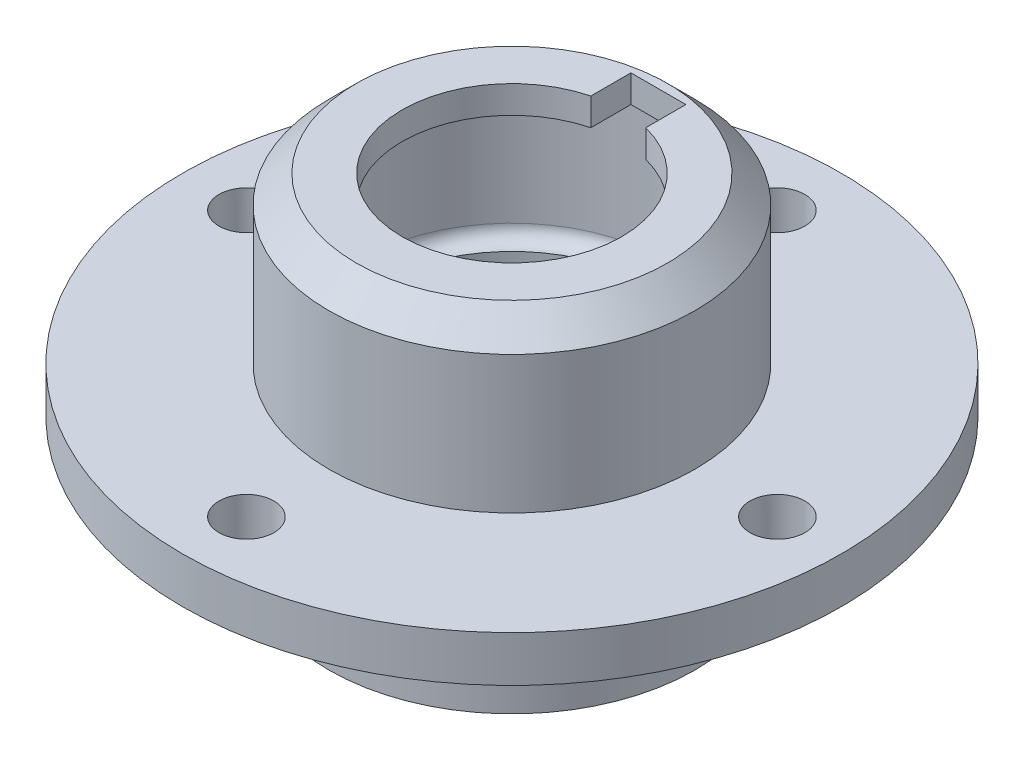
SolidWorks part; units mm, degrees
ref_plane "Front Plane" through (0, 0, 0) normal (0, 0, 1) x (1, 0, 0)
ref_plane "Top Plane" through (0, 0, 0) normal (0, 1, 0) x (1, 0, 0)
ref_plane "Right Plane" through (0, 0, 0) normal (1, 0, 0) x (0, 0, -1)
sketch "Sketch1" plane through (0, 0, 0) normal (0, 0, 1) x (1, 0, 0)
  line L0 (0, 106.7669) -> (0, -106.7669) construction
  line L1 (-115.3137, 0) -> (115.3137, 0) construction
  line L2 (30, 0) -> (40, 4)
  line L3 (40, 4) -> (40, 32)
  line L4 (40, 32) -> (72, 32)
  line L5 (72, 32) -> (72, 42)
  line L6 (72, 42) -> (40, 42)
  line L7 (40, 42) -> (40, 72)
  line L8 (40, 72) -> (34, 78)
  line L9 (34, 78) -> (0, 78)
  line L10 (0, 78) -> (0, 72)
  line L11 (0, 72) -> (33.3501, 72)
  line L12 (33.3501, 72) -> (33.3501, 44.9795)
  line L13 (30, 42) -> (30, 0)
  line L14 (30, 42) -> (0, 42)
  arc A0 (33.3501, 44.9795) -> (30, 42) centre (30.3501, 44.9795) cw
  point P4 (0, 0)
  point P7 (0, 0)
  dimension "D5" = 3
  dimension "D1" = 30
  dimension "D2" = 40
  dimension "D3" = 4
  dimension "D4" = 32
  dimension "D6" = 10
  dimension "D7" = 10
  dimension "D8" = 30
  dimension "D9" = 30
  dimension "D10" = 6
  dimension "D11" = 34
  dimension "D12" = 40
  dimension "D13" = 36
  dimension "D14" = 144
  dimension "D15" = 33.3501
revolve "Revolve2" add sketch "Sketch1" angle 360 about L0
sketch "Sketch2" plane through (0, 78, 0) normal (0, 1, 0) x (1, 0, 0)
  line L0 (0, 83.1447) -> (0, -83.1447) construction
  line L1 (-102.3474, 0) -> (102.3474, 0) construction
  line L2 (-6, 23.2379) -> (-6, 32)
  line L3 (-6, 32) -> (6, 32)
  line L4 (6, 32) -> (6, 23.2379)
  arc A0 (-6, 23.2379) -> (6, 23.2379) centre (0, 0) ccw
  point P5 (0, 0)
  point P11 (0, 0)
  dimension "D1" = 12
  dimension "D3" = 24
  dimension "D2" = 6
  dimension "D4" = 32
extrude "Cut-Extrude1" cut sketch "Sketch2" against normal through all both
sketch "Sketch3" plane through (0, 78, 0) normal (0, 1, 0) x (1, 0, 0)
  line L0 (-90.0818, 0) -> (90.0818, 0) construction
  line L1 (0, 80.9329) -> (0, -80.9329) construction
  circle A0 centre (0, 58) radius 6
  circle A1 centre (58, 0) radius 6
  circle A2 centre (0, -58) radius 6
  circle A3 centre (-58, 0) radius 6
  point P5 (0, 0)
  point P7 (0, 0)
  point P9 (0, 0)
  point P10 (0, 0)
  point P18 (0, 0)
  dimension "D1" = 12
  dimension "D2" = 58
  dimension "D4" = 58
  dimension "D5" = 116
  dimension "D3" = 4
extrude "Cut-Extrude2" cut sketch "Sketch3" against normal through all both
